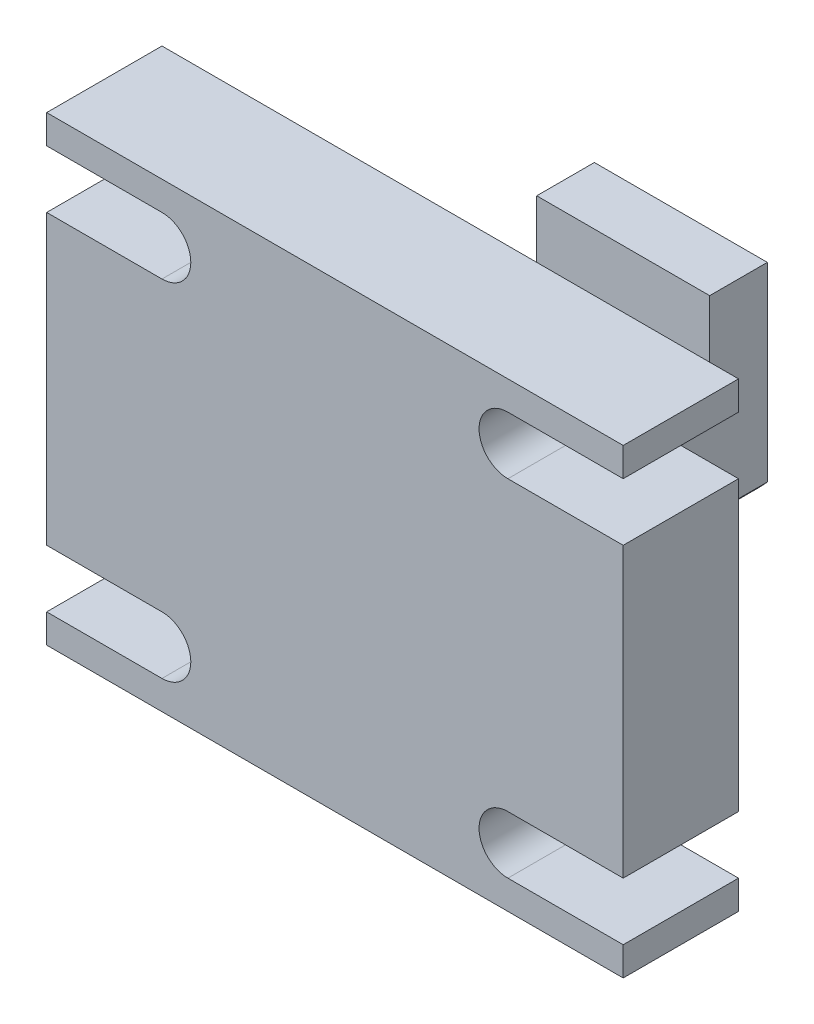
SolidWorks part; units mm, degrees
ref_plane "前基準面" through (0, 0, 0) normal (0, 0, 1) x (1, 0, 0)
ref_plane "上基準面" through (0, 0, 0) normal (0, 1, 0) x (1, 0, 0)
ref_plane "右基準面" through (0, 0, 0) normal (1, 0, 0) x (0, 0, -1)
sketch "草圖1" plane through (0, 0, 0) normal (0, 0, 1) x (1, 0, 0)
  line L1 (-50, 40) -> (50, 40)
  line L2 (-50, 40) -> (-50, -40)
  line L3 (-50, -40) -> (50, -40)
  line L4 (50, 40) -> (50, -40)
  line L5 (-50, 40) -> (50, -40) construction
  line L6 (-50, -40) -> (50, 40) construction
  line L7 (50, 35) -> (30, 35)
  line L8 (50, 35) -> (50, 25)
  line L9 (50, 25) -> (30, 25)
  line L11 (50, -25) -> (30, -25)
  line L12 (50, -25) -> (50, -35)
  line L13 (50, -35) -> (30, -35)
  line L15 (-50, 35) -> (-30, 35)
  line L16 (-50, 35) -> (-50, 25)
  line L17 (-50, 25) -> (-30, 25)
  line L19 (-50, -25) -> (-30, -25)
  line L20 (-50, -25) -> (-50, -35)
  line L21 (-50, -35) -> (-30, -35)
  arc A0 (-30, 25) -> (-30, 35) centre (-30, 30) ccw
  arc A1 (30, 35) -> (30, 25) centre (30, 30) ccw
  arc A2 (30, -25) -> (30, -35) centre (30, -30) ccw
  arc A3 (-30, -35) -> (-30, -25) centre (-30, -30) ccw
  point P0 (0, 0)
  dimension "D1" = 100
  dimension "D2" = 80
  dimension "D3" = 5
  dimension "D4" = 5
  dimension "D5" = 10
  dimension "D6" = 10
  dimension "D7" = 5
  dimension "D8" = 10
  dimension "D9" = 10
  dimension "D10" = 5
  dimension "D11" = 20
  dimension "D12" = 20
  dimension "D13" = 20
  dimension "D14" = 20
extrude "填料-伸長1" add sketch "草圖1" along normal blind 20 contours A3 L21 L2 L3 L4 L13 A2 L11 L9 A1 L7 L1 L15 A0 L17 L19
ref_plane "平面1" through (0, -5, 0) normal (0, -1, 0) x (-1, 0, 0)
sketch "草圖2" plane through (0, -5, 0) normal (0, -1, 0) x (-1, 0, 0)
  line L0 (50, 0) -> (-50, 0) construction
  line L1 (-25, 0) -> (25, 0)
  line L2 (15, 10) -> (15, 30)
  line L3 (15, 30) -> (-15, 30)
  line L4 (-15, 10) -> (-15, 30)
  line L5 (0, 16.5882) -> (0, -15.954) construction
  line L6 (-2.1412, 0) -> (2.7688, 0) construction
  arc A0 (-25, 0) -> (-15, 10) centre (-25, 10) ccw
  arc A1 (15, 10) -> (25, 0) centre (25, 10) ccw
  arc A2 (-15, 10) -> (-25, 0) centre (-25, 10) cw
  arc A3 (15, 10) -> (25, 0) centre (25, 10) ccw
  point P14 (0, 0)
  dimension "D3" = 20
  dimension "D4" = 20
  dimension "D1" = 30
  dimension "D2" = 30
extrude "填料-伸長2" add sketch "草圖2" against normal blind 10 contours A1 L2 L3 L4 A0 L1
sketch "草圖3" plane through (0, 0, -30) normal (0, 0, -1) x (-1, 0, 0)
  line L0 (15, 5) -> (-15, 5) construction
  line L1 (-15, 20) -> (15, 20)
  line L2 (-15, 20) -> (-15, -13)
  line L4 (15, 20) -> (15, -13)
  line L5 (0, 13.4282) -> (0, -43.5853) construction
  circle A1 centre (0, -13) radius 5
  arc A2 (-15, -13) -> (15, -13) centre (0, -0.4286) ccw
  dimension "D2" = 10
  dimension "D4" = 30
  dimension "D1" = 15
  dimension "D3" = 33
extrude "填料-伸長3" add sketch "草圖3" along normal blind 10
